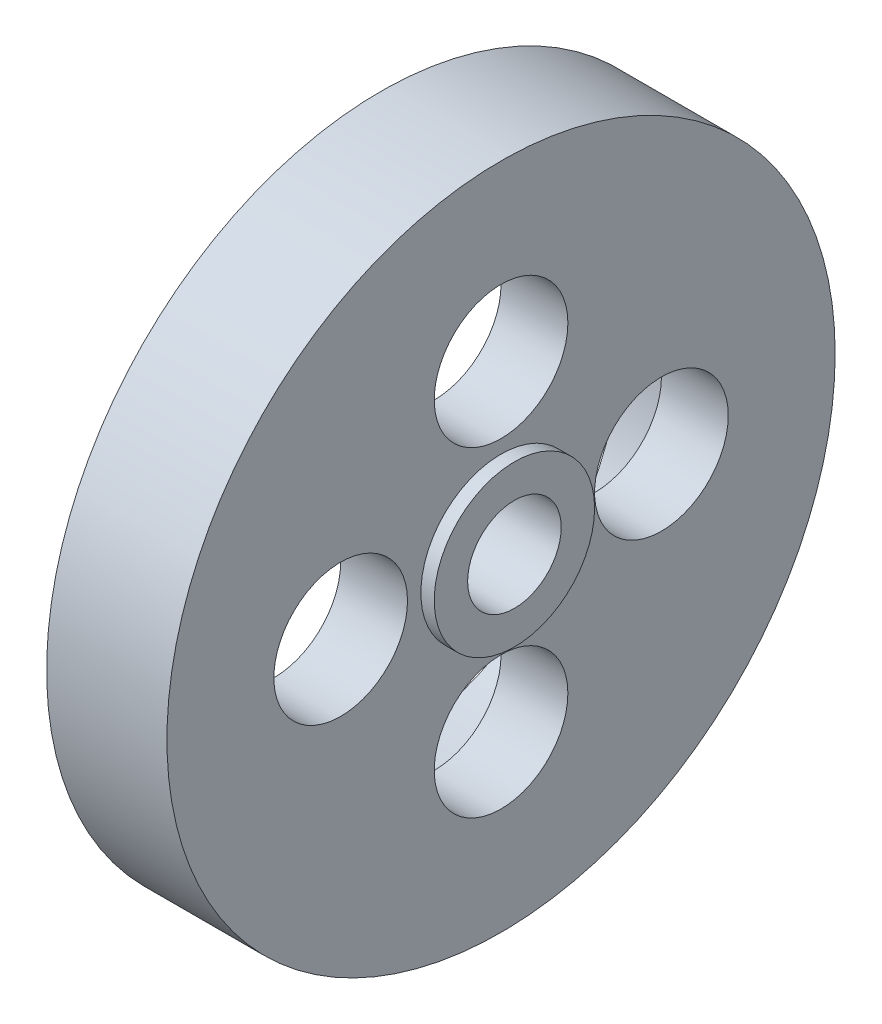
SolidWorks part; units mm, degrees
ref_plane "Front Plane" through (0, 0, 0) normal (0, 0, 1) x (1, 0, 0)
ref_plane "Top Plane" through (0, 0, 0) normal (0, 1, 0) x (1, 0, 0)
ref_plane "Right Plane" through (0, 0, 0) normal (1, 0, 0) x (0, 0, -1)
sketch "Sketch1" plane through (0, 0, 0) normal (1, 0, 0) x (0, 0, -1)
  circle A0 centre (0, 0) radius 25
  circle A1 centre (0, 0) radius 3.5
  dimension "D1" = 50
  dimension "D2" = 7
extrude "Boss-Extrude1" add sketch "Sketch1" along normal blind 10
sketch "Sketch2" plane through (10, 0, 0) normal (1, 0, 0) x (0, 0, -1)
  circle A0 centre (0, 0) radius 25 construction
  circle A2 centre (0, 0) radius 25
  circle A4 centre (0, 0) radius 6
  dimension "D1" = 12
extrude "Cut-Extrude2" cut sketch "Sketch2" against normal blind 1
sketch "Sketch3" plane through (9, 0, 0) normal (1, 0, 0) x (0, 0, -1)
  circle A0 centre (0, 0) radius 12 construction
  circle A1 centre (0, 12) radius 5
  circle A2 centre (12, 0) radius 5
  circle A3 centre (0, -12) radius 5
  circle A4 centre (-12, 0) radius 5
  circle A5 centre (0, 0) radius 6 construction
  point P14 (0, 0)
  dimension "D1" = 24
  dimension "D2" = 10
  dimension "D4" = 12
  dimension "D5" = 12
  dimension "D3" = 4
extrude "Cut-Extrude3" cut sketch "Sketch3" against normal through all
sketch "Sketch4" plane through (0, 0, 0) normal (-1, 0, 0) x (0, 0, 1)
  circle A0 centre (0, 0) radius 18
  dimension "D1" = 36
extrude "Cut-Extrude4" cut sketch "Sketch4" against normal blind 4
